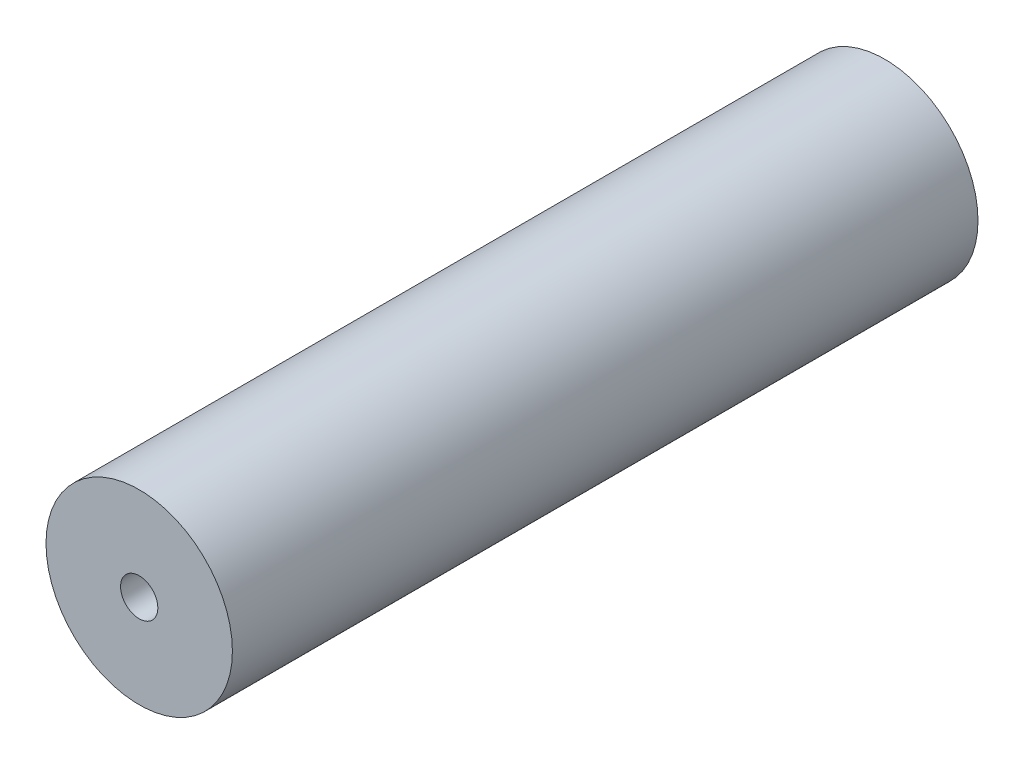
SolidWorks part; units mm, degrees
ref_plane "Ön Düzlem" through (0, 0, 0) normal (0, 0, 1) x (1, 0, 0)
ref_plane "Üst Düzlem" through (0, 0, 0) normal (0, 1, 0) x (1, 0, 0)
ref_plane "Sağ Düzlem" through (0, 0, 0) normal (1, 0, 0) x (0, 0, -1)
sketch "Çizim1" plane through (0, 0, 0) normal (0, 0, 1) x (1, 0, 0)
  circle A0 centre (0, 0) radius 10
extrude "Yükseklik-Ekstrüzyon1" add sketch "Çizim1" along normal blind 80
sketch "Çizim2" plane through (0, 0, 80) normal (0, 0, 1) x (1, 0, 0)
  circle A0 centre (0, 0) radius 2
extrude "Kes-Ekstrüzyon1" cut sketch "Çizim2" against normal blind 80
